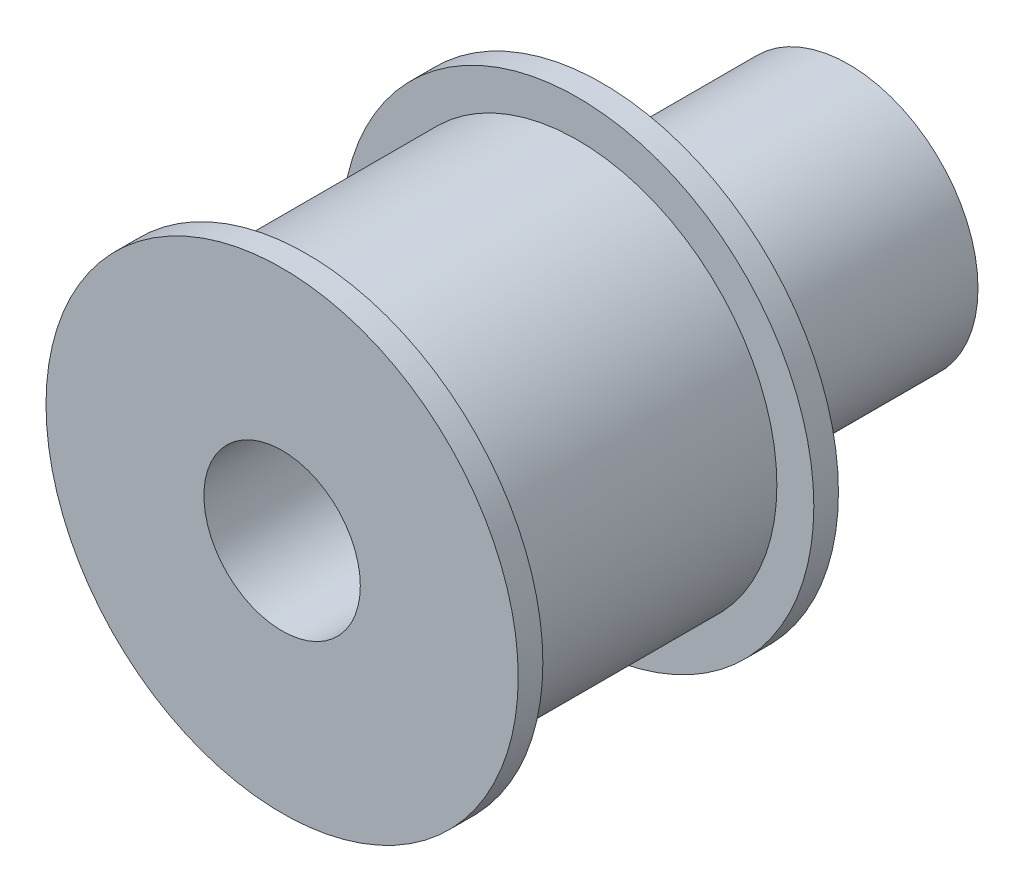
SolidWorks part; units mm, degrees
ref_plane "Front Plane" through (0, 0, 0) normal (0, 0, 1) x (1, 0, 0)
ref_plane "Top Plane" through (0, 0, 0) normal (0, 1, 0) x (1, 0, 0)
ref_plane "Right Plane" through (0, 0, 0) normal (1, 0, 0) x (0, 0, -1)
sketch "Sketch1" plane through (0, 0, 0) normal (0, 1, 0) x (1, 0, 0)
  line L0 (0, 0) -> (0, 161.9291) construction
  line L1 (0, 23) -> (-5.25, 23)
  line L2 (-5.25, 23) -> (-5.25, 13)
  line L3 (-5.25, 13) -> (-9.5851, 13)
  line L4 (-9.5851, 13) -> (-9.5851, 12)
  line L5 (-9.5851, 12) -> (-8.0851, 12)
  line L6 (-8.0851, 12) -> (-8.0851, 1)
  line L7 (-8.0851, 1) -> (-9.5851, 1)
  line L8 (-9.5851, 1) -> (-9.5851, 0)
  line L9 (-9.5851, 0) -> (0, 0)
  line L10 (0, 0) -> (0, 23)
  line L11 (-9.5851, 12) -> (-9.5851, 1) construction
  dimension "D1" = 8.0851
  dimension "D2" = 1.5
  dimension "D3" = 11
  dimension "D4" = 1
  dimension "D5" = 1
  dimension "D6" = 10
  dimension "D7" = 5.25
revolve "Revolve1" add sketch "Sketch1" angle 360 about L10
sketch "Sketch2" plane through (0, 0, 0) normal (0, 0, 1) x (1, 0, 0)
  circle A0 centre (0, 0) radius 3.175
  circle A1 centre (0, 0) radius 9.5851 construction
  dimension "D1" = 6.35
extrude "Cut-Extrude1" cut sketch "Sketch2" against normal through all
sketch "Sketch3" plane through (0, 0, 0) normal (0, 1, 0) x (1, 0, 0)
  line L0 (0, 23) -> (0, 13) construction
  line L1 (5.25, 23) -> (-5.25, 23) construction
  circle A0 centre (0, 18) radius 1.5
  dimension "D1" = 5
  dimension "D2" = 3
extrude "Cut-Extrude2" cut sketch "Sketch3" against normal through all
sketch "Sketch4" plane through (0, 0, 0) normal (1, 0, 0) x (0, 0, -1)
  line L0 (23, 0) -> (13, 0) construction
  line L1 (23, -5.25) -> (23, 5.25) construction
  circle A0 centre (18, 0) radius 1.5
  dimension "D1" = 5
  dimension "D2" = 3
extrude "Cut-Extrude3" cut sketch "Sketch4" against normal through all
ref_plane "Plane1" through (0, 0, -6.5) normal (0, 0, 1) x (1, 0, 0)
equation "\"teeth\"= 10"
equation "\"pitch\"= 0.2in"
equation "\"pitch diameter\"= \"teeth\" * \"pitch\" / pi"
equation "\"D1@Sketch1\"=\"pitch diameter\"/2"
